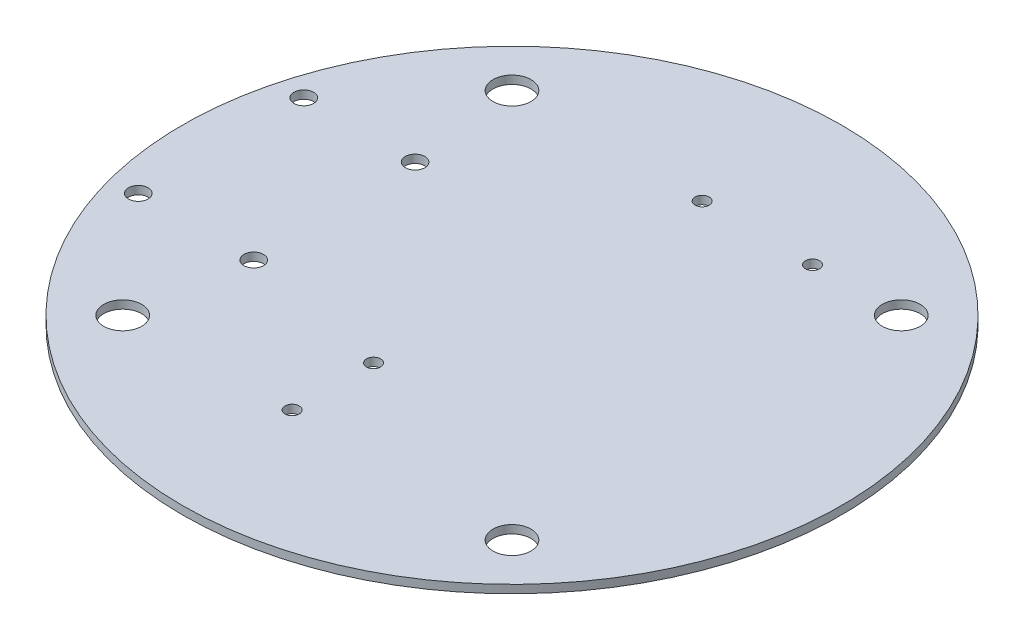
SolidWorks part; units mm, degrees
ref_plane "Front Plane" through (0, 0, 0) normal (0, 0, 1) x (1, 0, 0)
ref_plane "Top Plane" through (0, 0, 0) normal (0, 1, 0) x (1, 0, 0)
ref_plane "Right Plane" through (0, 0, 0) normal (1, 0, 0) x (0, 0, -1)
sketch "Sketch1" plane through (0, 0, 0) normal (0, 1, 0) x (1, 0, 0)
  circle A0 centre (0, 0) radius 60.7
  dimension "PCBdiam" = 121.4
extrude "Boss-Extrude1" add sketch "Sketch1" along normal blind 1.5
hole_wizard "M6 Clearance Hole1" positions "Sketch2" profile "Sketch4" hole size "M6" standard "ANSI Metric" end condition through all
sketch "Sketch2" plane through (0, 1.5, 0) normal (0, 1, 0) x (1, 0, 0)
  line L0 (0, 0) -> (-28.5457, 28.5457) construction
  line L1 (-35.8503, -35.8503) -> (0, 0) construction
  line L3 (0, 0) -> (-73.422, 0) construction
  circle A0 centre (0, 0) radius 60.7 construction
  ellipse E2 centre (-116.4291, -176.9435) end of major axis (-117.7556, -176.0714) minor radius 1.3748
  ellipse E3 centre (-116.4291, -176.9435) end of major axis (-115.1026, -177.8157) minor radius 1.3748
  point P7 (-35.8503, -35.8503)
  dimension "D1" = 0
  dimension "holeRadius" = 50.7
  dimension "D2" = 45
sketch "Sketch4" plane through (-35.8503, 1.5, 35.8503) normal (1, 0, 0) x (0, 0, 1)
  line L0 (0, 0) -> (0, 1.5)
  line L1 (0, 1.5) -> (3.5, 1.5)
  line L2 (3.5, 1.5) -> (3.5, 0)
  line L5 (3.5, 0) -> (0, 0)
  line L11 (0, -6.35) -> (0, 107.95) construction
  dimension "Thru Hole Dia." = 7
  dimension "Thru Hole Depth" = 1.5
pattern_circular "CirPattern1" count 4 over 360 about axis through (0, 0, 0) along (0, 1, 0) of "M6 Clearance Hole1"
sketch "Teensy Outline" plane through (0, 1.5, 0) normal (0, 1, 0) x (1, 0, 0)
  line L1 (-27.654, 45.7) -> (-10, 45.7)
  line L2 (-27.654, 45.7) -> (-27.654, -12.72)
  line L3 (-27.654, -12.72) -> (-10, -12.72)
  line L4 (-10, 45.7) -> (-10, -12.72)
  circle A1 centre (0, 0) radius 60.7 construction
  dimension "D1" = 17.654
  dimension "D2" = 58.42
  dimension "D3" = 10
  dimension "D4" = 15
sketch "BMP390 Outline" plane through (0, 1.5, 0) normal (0, 1, 0) x (1, 0, 0)
  line L0 (19.61, 49.7) -> (-3.25, 49.7) construction
  line L2 (22.15, 51.04) -> (-3.25, 51.04)
  line L3 (-3.25, 51.04) -> (-3.25, 33.26)
  line L4 (22.15, 33.26) -> (-3.25, 33.26)
  line L6 (22.15, 51.04) -> (22.15, 33.26)
  line L7 (19.61, 49.7) -> (19.61, 33.26) construction
  line L8 (-27.654, 45.7) -> (-10, 45.7) construction
  line L9 (-10, 45.7) -> (-10, -12.72) construction
  dimension "D1" = 17.78
  dimension "D2" = 25.4
  dimension "D3" = 1.34
  dimension "D4" = 4
  dimension "D5" = 6.75
  dimension "D6" = 5.08
sketch "NEO-6M Outline" plane through (0, 1.5, 0) normal (0, 1, 0) x (1, 0, 0)
  line L0 (-48.84, 17.78) -> (-48.84, 15.24) construction
  line L1 (-56.34, 17.78) -> (-30, 17.78)
  line L2 (-56.34, 17.78) -> (-56.34, -17.78)
  line L3 (-56.34, -17.78) -> (-30, -17.78)
  line L4 (-30, 17.78) -> (-30, -17.78)
  line L5 (-48.84, 15.24) -> (-37.5, 15.24) construction
  line L6 (-37.5, 15.24) -> (-37.5, 17.78) construction
  point P4 (-30, 0)
  point P9 (-43.17, 15.24)
  point P11 (-43.17, 17.78)
  dimension "D1" = 26.34
  dimension "D2" = 35.56
  dimension "D3" = 30
  dimension "D4" = 7.5
  dimension "D5" = 2.54
sketch "Accel, gyro outline" plane through (0, 1.5, 0) normal (0, 1, 0) x (1, 0, 0)
  line L0 (47.32, 26.44) -> (27, 26.44) construction
  line L1 (52.4, 27.78) -> (27, 27.78)
  line L2 (27, 27.78) -> (27, 10)
  line L3 (52.4, 10) -> (27, 10)
  line L4 (52.4, 27.78) -> (52.4, 10)
  line L5 (47.32, 26.44) -> (47.32, 11.34) construction
  line L6 (27, 18.89) -> (52.4, 18.89) construction
  line L7 (47.32, 11.34) -> (27, 11.34) construction
  dimension "D1" = 17.78
  dimension "D2" = 25.4
  dimension "D3" = 1.34
  dimension "D4" = 5.08
  dimension "D5" = 10
  dimension "D6" = 27
sketch "Airspeed sensor outline" plane through (0, 1.5, 0) normal (0, 1, 0) x (1, 0, 0)
  line L0 (-22.654, -23.8503) -> (-29.154, -23.8503) construction
  line L1 (-22.654, -17.8503) -> (-2.654, -17.8503)
  line L2 (-22.654, -17.8503) -> (-22.654, -37.8503)
  line L3 (-22.654, -37.8503) -> (-2.654, -37.8503)
  line L4 (-2.654, -17.8503) -> (-2.654, -37.8503)
  line L5 (-29.154, -23.8503) -> (-29.154, -31.8503) construction
  line L6 (-29.154, -31.8503) -> (-22.654, -31.8503) construction
  line L7 (-27.654, 45.7) -> (-27.654, -12.72) construction
  circle A0 centre (-35.8503, -35.8503) radius 3.5 construction
  point P8 (-29.154, -27.8503)
  point P9 (-22.654, -27.8503)
  dimension "D1" = 20
  dimension "D2" = 20
  dimension "D3" = 6.5
  dimension "D4" = 8
  dimension "D5" = 5
  dimension "D6" = 2
sketch "Xbee outline" plane through (0, 1.5, 0) normal (0, 1, 0) x (1, 0, 0)
  line L0 (9.25, 2.26) -> (9.25, -14.74) construction
  line L1 (4.625, -14.74) -> (13.875, -14.74)
  line L2 (13.875, -14.74) -> (21.5, -8.24)
  line L3 (21.5, -8.24) -> (21.5, 18.26)
  line L4 (21.5, 18.26) -> (-3, 18.26)
  line L5 (-3, -8.24) -> (-3, 18.26)
  line L6 (4.625, -14.74) -> (-3, -8.24)
  line L7 (9.25, -20.0658) -> (9.25, -49.74) construction
  line L8 (22.15, 33.26) -> (-3.25, 33.26) construction
  line L9 (-10, 45.7) -> (-10, -12.72) construction
  line L10 (14.75, -49.74) -> (14.75, -14.74) construction
  line L11 (14.75, -49.74) -> (3.75, -49.74) construction
  line L12 (3.75, -49.74) -> (3.75, -14.74) construction
  line L13 (14.75, -14.74) -> (3.75, -14.74) construction
  point P7 (9.25, 18.26)
  point P11 (9.25, -14.74)
  dimension "D1" = 24.5
  dimension "D2" = 33
  dimension "D3" = 26.5
  dimension "D4" = 9.25
  dimension "D5" = 16
  dimension "D6" = 35
  dimension "D7" = 11
  dimension "D8" = 0
  dimension "D9" = 15
  dimension "D10" = 7
hole_wizard "M2 Clearance Hole1" positions "Sketch20" profile "Sketch19" hole size "M2" standard "ANSI Metric" end condition through all
sketch "Sketch20" plane through (0, 1.5, 0) normal (0, 1, 0) x (1, 0, 0)
  circle A0 centre (-0.71, 35.73) radius 1.2493 construction
  circle A1 centre (19.61, 35.73) radius 1.2493 construction
  circle A2 centre (-5.154, -20.3503) radius 1.25 construction
  circle A3 centre (-5.154, -20.3503) radius 1.25 construction
  circle A4 centre (-5.154, -35.3503) radius 1.25 construction
  circle A5 centre (-5.154, -35.3503) radius 1.25 construction
  point P1 (-0.71, 35.73)
  point P7 (19.61, 35.73)
  point P13 (-5.154, -20.3503)
  point P16 (-5.154, -35.3503)
sketch "Sketch19" plane through (-0.71, 1.5, -35.73) normal (1, 0, 0) x (0, 0, 1)
  line L0 (0, 0) -> (0, 1.5)
  line L1 (0, 1.5) -> (1.3, 1.5)
  line L2 (1.3, 1.5) -> (1.3, 0)
  line L5 (1.3, 0) -> (0, 0)
  line L11 (0, -6.35) -> (0, 107.95) construction
  dimension "Thru Hole Dia." = 2.6
  dimension "Thru Hole Depth" = 1.5
hole_wizard "M3 Clearance Hole2" positions "Sketch21" profile "Sketch22" hole size "M3" standard "ANSI Metric" end condition through all
sketch "Sketch21" plane through (0, 1.5, 0) normal (0, 1, 0) x (1, 0, 0)
  point P0 (-53.8645, 15.5117)
  point P3 (-53.8645, -14.9683)
  point P6 (-32.6045, -14.9683)
  point P9 (-33.3665, 15.5117)
sketch "Sketch22" plane through (-53.8645, 1.5, -15.5117) normal (1, 0, 0) x (0, 0, 1)
  line L0 (0, 0) -> (0, 1.5)
  line L1 (0, 1.5) -> (1.8, 1.5)
  line L2 (1.8, 1.5) -> (1.8, 0)
  line L5 (1.8, 0) -> (0, 0)
  line L11 (0, -6.35) -> (0, 107.95) construction
  dimension "Thru Hole Dia." = 3.6
  dimension "Thru Hole Depth" = 1.5
